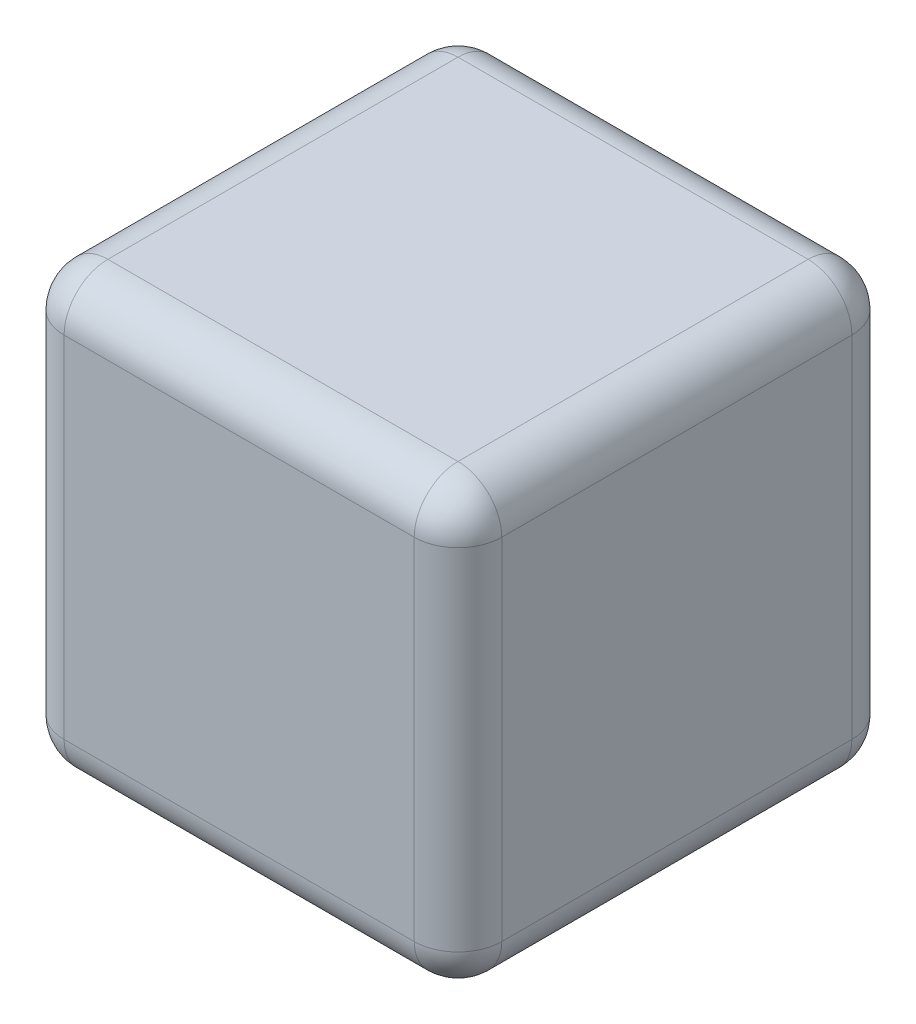
SolidWorks part; units mm, degrees
ref_plane "Front Plane" through (0, 0, 0) normal (0, 0, 1) x (1, 0, 0)
ref_plane "Top Plane" through (0, 0, 0) normal (0, 1, 0) x (1, 0, 0)
ref_plane "Right Plane" through (0, 0, 0) normal (1, 0, 0) x (0, 0, -1)
sketch "Sketch1" plane through (0, 0, 0) normal (0, 1, 0) x (1, 0, 0)
  line L1 (0, 0) -> (63.5, 0)
  line L2 (0, 0) -> (0, -63.5)
  line L3 (0, -63.5) -> (63.5, -63.5)
  line L4 (63.5, 0) -> (63.5, -63.5)
extrude "Boss-Extrude1" add sketch "Sketch1" along normal blind 63.5
fillet "Fillet1" radius 6.35 12 edges at (0, 31.75, 63.5) (63.5, 31.75, 63.5) (31.75, 0, 63.5) (31.75, 63.5, 0) (63.5, 63.5, 31.75) (31.75, 63.5, 63.5) (0, 63.5, 31.75) (63.5, 0, 31.75) (63.5, 31.75, 0) (0, 31.75, 0) (0, 0, 31.75) (31.75, 0, 0)
